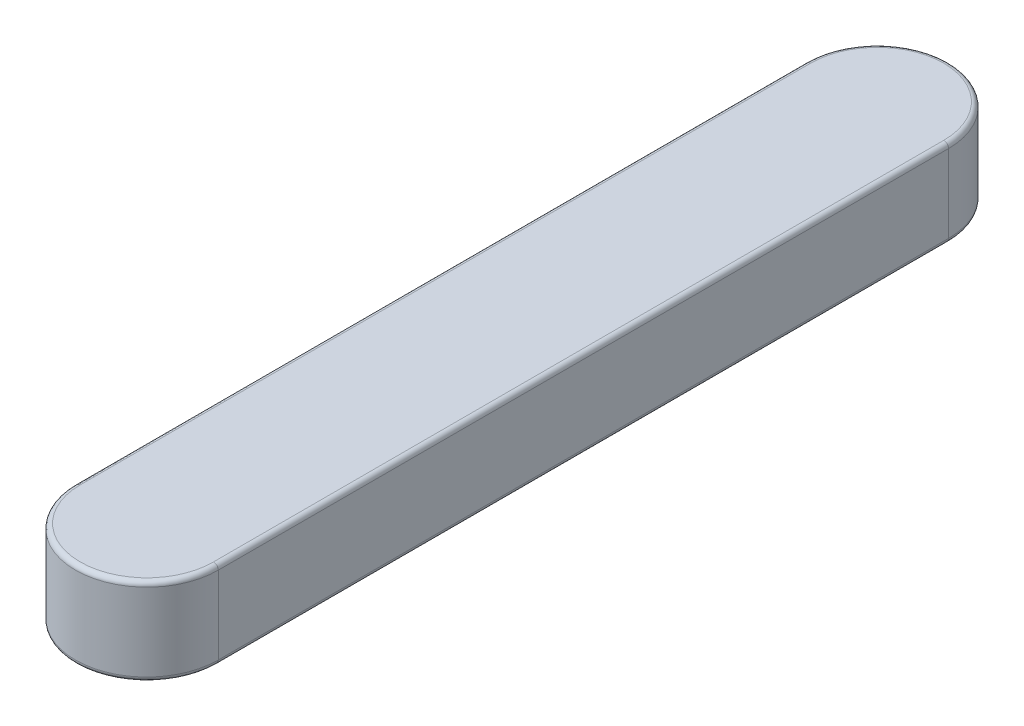
SolidWorks part; units mm, degrees
material "AISI 304"
ref_plane "Спереди" through (0, 0, 0) normal (0, 0, 1) x (1, 0, 0)
ref_plane "Сверху" through (0, 0, 0) normal (0, 1, 0) x (1, 0, 0)
ref_plane "Справа" through (0, 0, 0) normal (1, 0, 0) x (0, 0, -1)
sketch "Эскиз1" plane through (0, 0, 0) normal (0, 1, 0) x (1, 0, 0)
  line L0 (0, 0) -> (0, 92) construction
  line L1 (-9, 0) -> (-9, 92)
  line L2 (9, 0) -> (9, 92)
  line L3 (0, -9) -> (0, 101) construction
  arc A0 (-9, 0) -> (9, 0) centre (0, 0) ccw
  arc A1 (9, 92) -> (-9, 92) centre (0, 92) ccw
  point P3 (0, 46)
  dimension "D1" = 9
  dimension "D2" = 92
  dimension "D3" = 110
  dimension "D4" = 18
extrude "Бобышка-Вытянуть1" add sketch "Эскиз1" along normal blind 11
fillet "Скругление1" radius 0.6 8 edges at (9, 0, -46) (0, 0, -101) (-9, 0, -46) (0, 0, 9) (-9, 11, -46) (0, 11, -101) (9, 11, -46) (0, 11, 9)
